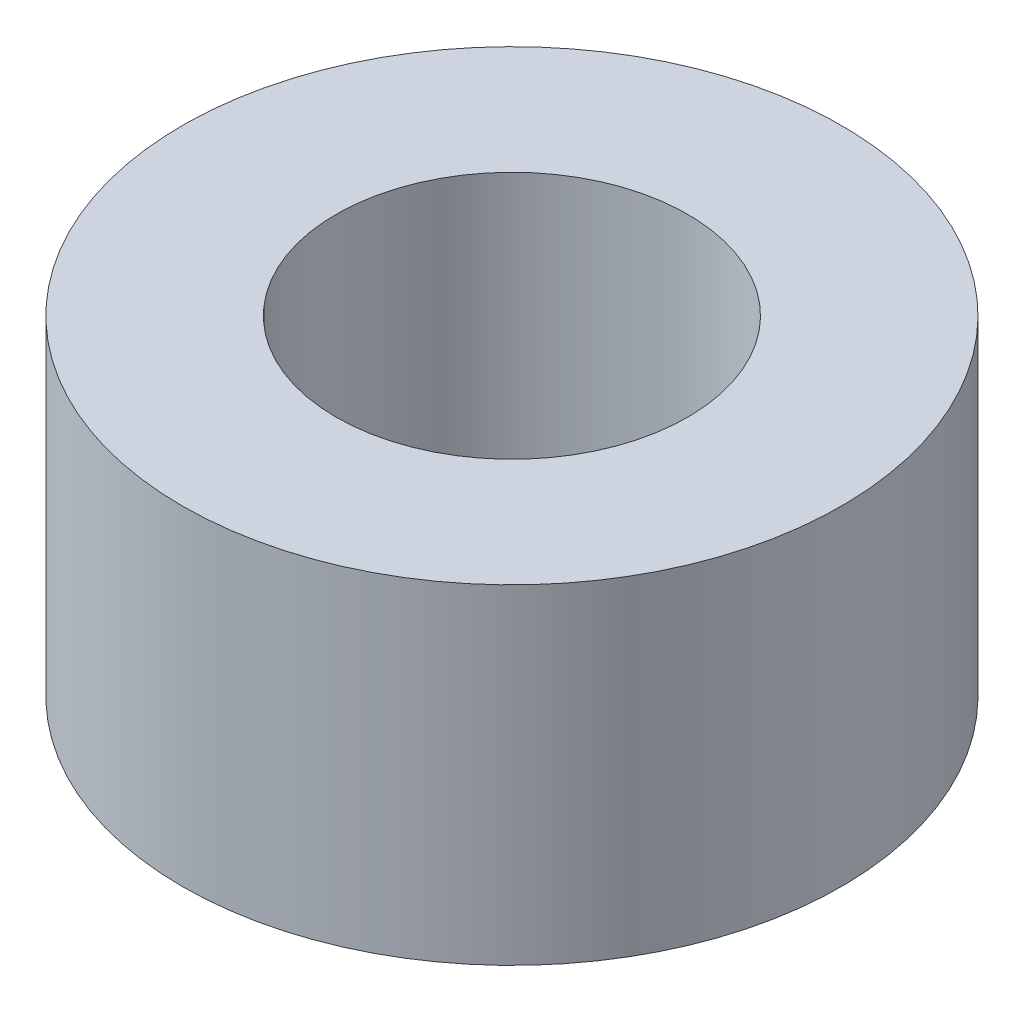
SolidWorks part; units mm, degrees
ref_plane "Front Plane" through (0, 0, 0) normal (0, 0, 1) x (1, 0, 0)
ref_plane "Top Plane" through (0, 0, 0) normal (0, 1, 0) x (1, 0, 0)
ref_plane "Right Plane" through (0, 0, 0) normal (1, 0, 0) x (0, 0, -1)
sketch "Sketch1" plane through (0, 0, 0) normal (0, 1, 0) x (1, 0, 0)
  circle A1 centre (0, 0) radius 1.6
  circle A3 centre (0, 0) radius 3
  dimension "D2" = 3.2
  dimension "D4" = 6
extrude "Boss-Extrude1" add sketch "Sketch1" along normal blind 3 contours A1
